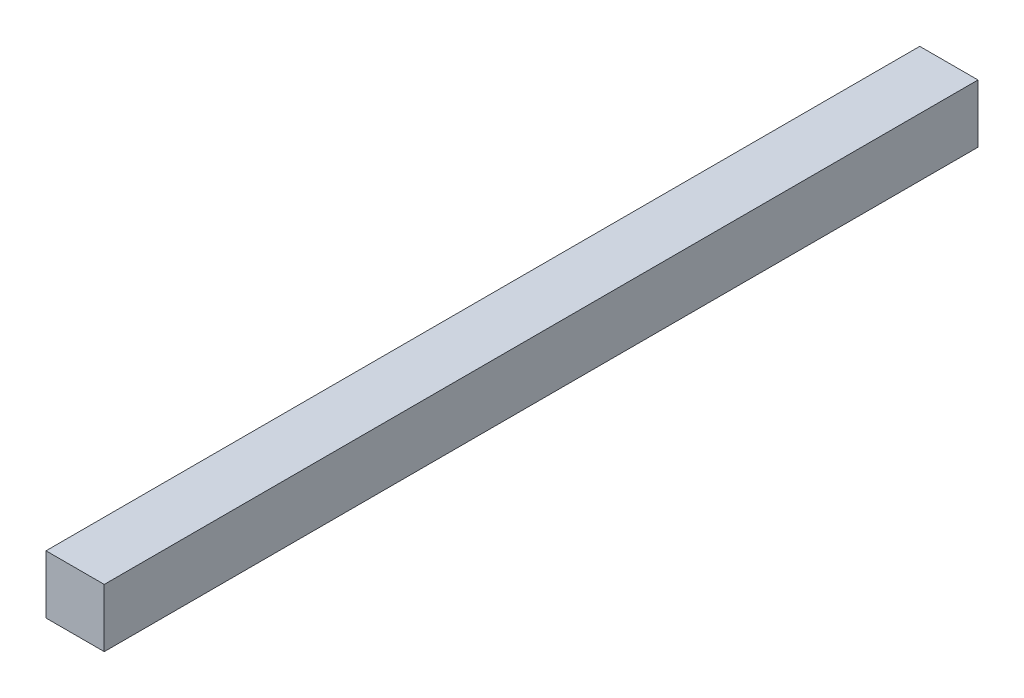
SolidWorks part; units mm, degrees
ref_plane "前基準面" through (0, 0, 0) normal (0, 0, 1) x (1, 0, 0)
ref_plane "上基準面" through (0, 0, 0) normal (0, 1, 0) x (1, 0, 0)
ref_plane "右基準面" through (0, 0, 0) normal (1, 0, 0) x (0, 0, -1)
sketch "草圖1" plane through (0, 0, 0) normal (0, 0, 1) x (1, 0, 0)
  line L1 (-10, 10) -> (10, 10)
  line L2 (-10, 10) -> (-10, -10)
  line L3 (-10, -10) -> (10, -10)
  line L4 (10, 10) -> (10, -10)
  point P4 (0, 10)
  point P6 (-10, 0)
  dimension "D1" = 20
  dimension "D2" = 20
extrude "填料-伸長1" add sketch "草圖1" along normal blind 300
sketch "草圖2" plane through (0, 10, 0) normal (0, 1, 0) x (1, 0, 0)
  line L0 (-10, -150) -> (10, -150) construction
  line L1 (-10, -300) -> (-10, 0) construction
  line L2 (10, -300) -> (10, 0) construction
  line L3 (-10, -245) -> (10, -245) construction
  line L4 (10, -300) -> (-10, -300) construction
  line L5 (-10, -55) -> (10, -55) construction
  dimension "D1" = 55
